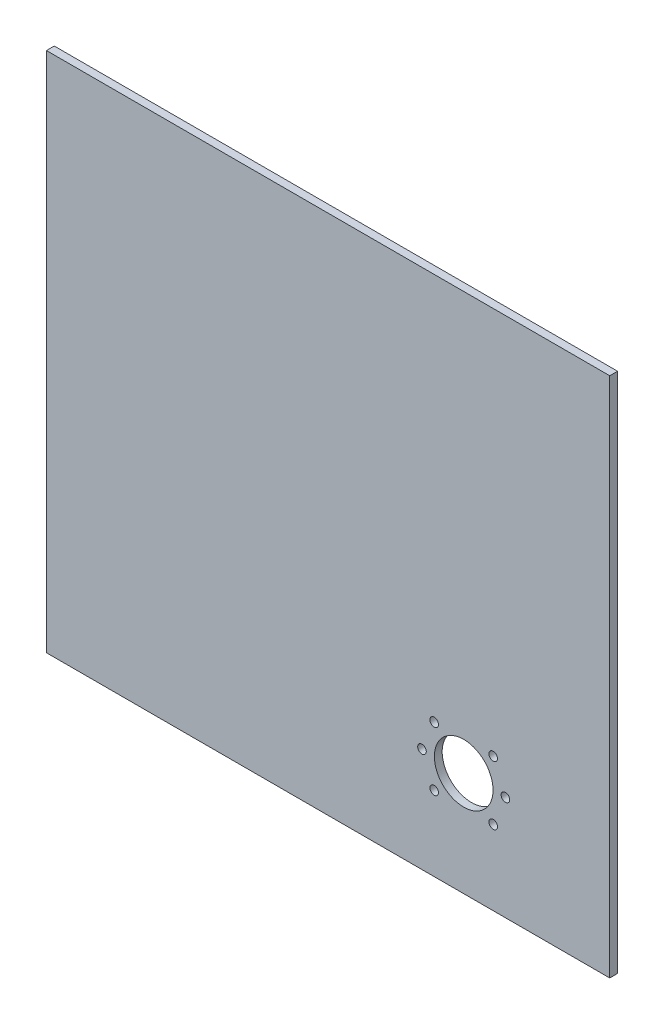
SolidWorks part; units mm, degrees
ref_plane "前视基准面" through (0, 0, 0) normal (0, 0, 1) x (1, 0, 0)
ref_plane "上视基准面" through (0, 0, 0) normal (0, 1, 0) x (1, 0, 0)
ref_plane "右视基准面" through (0, 0, 0) normal (1, 0, 0) x (0, 0, -1)
sketch "草图1" plane through (0, 0, 0) normal (0, 0, 1) x (1, 0, 0)
  line L1 (-108, 100) -> (108, 100)
  line L2 (-108, 100) -> (-108, -100)
  line L3 (-108, -100) -> (108, -100)
  line L4 (108, 100) -> (108, -100)
  line L5 (-108, 100) -> (108, -100) construction
  line L6 (-108, -100) -> (108, 100) construction
  point P0 (0, 0)
  dimension "D1" = 216
  dimension "D2" = 200
extrude "凸台-拉伸1" add sketch "草图1" along normal blind 3
sketch "草图2" plane through (0, 0, 3) normal (0, 0, 1) x (1, 0, 0)
  line L0 (-108, -100) -> (108, -100) construction
  line L1 (-108, 100) -> (-108, -100) construction
  circle A0 centre (52, -60) radius 11.25
  dimension "D1" = 22.5
  dimension "D2" = 40
  dimension "D3" = 160
extrude "切除-拉伸1" cut sketch "草图2" against normal through all
sketch "草图3" plane through (0, 0, 3) normal (0, 0, 1) x (1, 0, 0)
  circle A0 centre (52, -60) radius 16 construction
  circle A1 centre (36, -60) radius 2
  circle A2 centre (40.6863, -48.6863) radius 2
  circle A4 centre (63.3137, -48.6863) radius 2
  circle A5 centre (68, -60) radius 2
  circle A6 centre (63.3137, -71.3137) radius 2
  circle A8 centre (40.6863, -71.3137) radius 2
  circle A9 centre (52, -44) radius 2
  circle A10 centre (52, -76) radius 2
  point P21 (52, -60)
  dimension "D1" = 8
hole_wizard "M4 螺纹孔的螺纹孔钻头1" positions "3D草图1" profile "草图4" hole size "M4" standard "GB" end condition through all
sketch3d "3D草图1"
  point P0 (36, -60, 3)
  point P3 (40.6863, -48.6863, 3)
  point P6 (40.6863, -71.3137, 3)
  point P9 (63.3137, -48.6863, 3)
  point P12 (68, -60, 3)
  point P15 (63.3137, -71.3137, 3)
sketch "草图4" plane through (36, -60, 3) normal (1, 0, 0) x (0, -1, 0)
  line L0 (0, 0) -> (0, 3)
  line L1 (0, 3) -> (1.65, 3)
  line L2 (1.65, 3) -> (1.65, 0)
  line L5 (1.65, 0) -> (0, 0)
  line L11 (0, -6.35) -> (0, 107.95) construction
  dimension "通孔孔直径" = 3.3
  dimension "通孔孔深度" = 3
